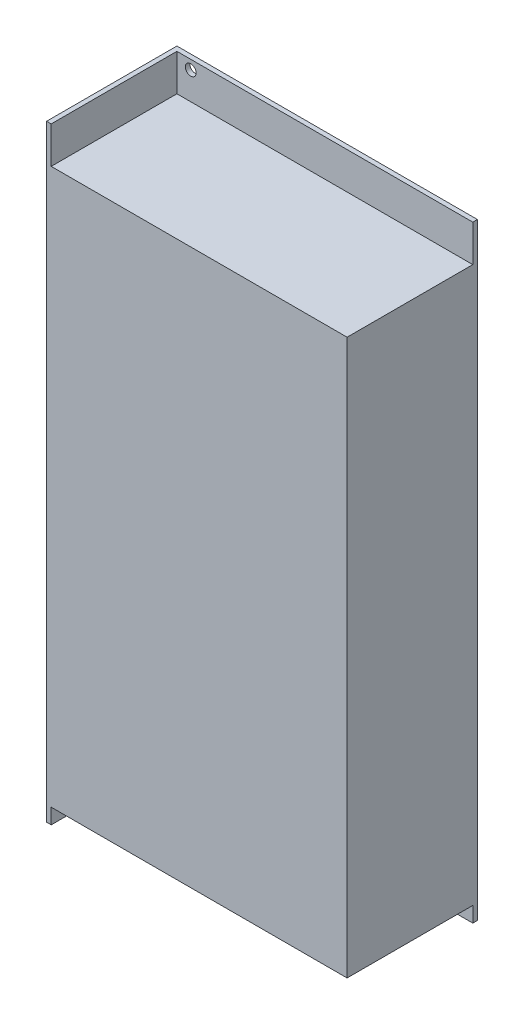
SolidWorks part; units mm, degrees
ref_plane "Plan de face" through (0, 0, 0) normal (0, 0, 1) x (1, 0, 0)
ref_plane "Plan de dessus" through (0, 0, 0) normal (0, 1, 0) x (1, 0, 0)
ref_plane "Plan de droite" through (0, 0, 0) normal (1, 0, 0) x (0, 0, -1)
sketch "Esquisse1" plane through (0, 0, 0) normal (0, 0, 1) x (1, 0, 0)
  line L0 (-5, -195.25) -> (-5, -198)
  line L1 (0, 0) -> (-98, 0)
  line L2 (0, 0) -> (0, -198)
  line L3 (0, -198) -> (-98, -198)
  line L4 (-98, 0) -> (-98, -198)
  line L5 (-5, -198) -> (-8.5, -198)
  line L6 (-8.5, -198) -> (-8.5, -195.25)
  circle A0 centre (-92, -3) radius 1.75
  circle A1 centre (-6.75, -195.25) radius 1.75
  dimension "D3" = 3.5
  dimension "D4" = 3.5
  dimension "D1" = 98
  dimension "D2" = 198
  dimension "D5" = 3
  dimension "D6" = 6
  dimension "D7" = 6.75
  dimension "D8" = 2.75
extrude "Boss.-Extru.1" add sketch "Esquisse1" along normal blind 1.5 contours A1 L0 L3 L2 L1 L4 L6 A0
sketch "Esquisse2" plane through (0, 0, 1.5) normal (0, 0, 1) x (1, 0, 0)
  line L0 (0, 0) -> (-98, 0) construction
  line L1 (-98, -198) -> (-96.5, -198)
  line L2 (-98, -198) -> (-98, 0)
  line L3 (-98, 0) -> (-96.5, 0)
  line L4 (-96.5, -198) -> (-96.5, 0)
  line L5 (0, 0) -> (0, -198) construction
  line L6 (-96.5, -12) -> (0, -12)
  line L7 (-96.5, -12) -> (-96.5, -193)
  line L8 (-96.5, -193) -> (0, -193)
  line L9 (0, -12) -> (0, -193)
  line L10 (-8.5, -198) -> (-98, -198) construction
  line M8 (0, -198) -> (0, 0)
  line M9 (0, 0) -> (-98, 0)
  line M10 (-98, 0) -> (-98, -198)
  line M11 (-98, -198) -> (-8.5, -198)
  dimension "D1" = 1.5
  dimension "D2" = 5
  dimension "D3" = 12
extrude "Boss.-Extru.2" add sketch "Esquisse2" along normal blind 41 contours L4 L8 L6 M8 | L4 M11 M9 M10
